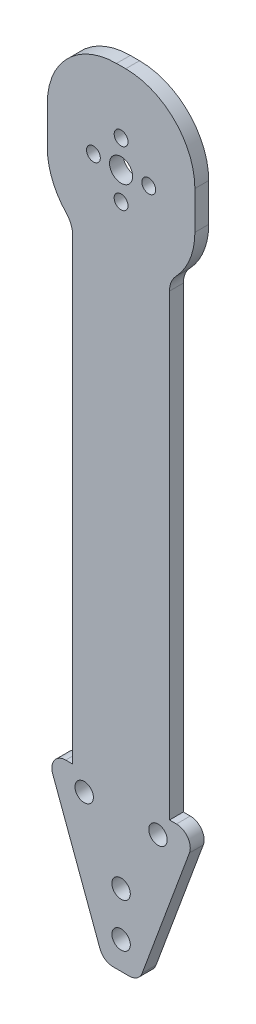
SolidWorks part; units mm, degrees
ref_plane "Alzado" through (0, 0, 0) normal (0, 0, 1) x (1, 0, 0)
ref_plane "Planta" through (0, 0, 0) normal (0, 1, 0) x (1, 0, 0)
ref_plane "Vista lateral" through (0, 0, 0) normal (1, 0, 0) x (0, 0, -1)
sketch "Croquis1" plane through (0, 0, 0) normal (0, 0, 1) x (1, 0, 0)
  line L0 (0, 0) -> (0, 170) construction
  line L1 (1.7626, 0) -> (-1.7626, 0)
  line L2 (-4.5763, 1.9593) -> (-14.816, 29.6448)
  line L3 (-12.0023, 33.6854) -> (-10.5, 33.6854)
  line L4 (-10.5, 33.6854) -> (-10.5, 133)
  line L6 (-16, 146.775) -> (-16, 155)
  line L7 (-1, 170) -> (1, 170)
  line L8 (16, 146.775) -> (16, 155)
  line L10 (10.5, 33.6854) -> (10.5, 133)
  line L11 (12.0023, 33.6854) -> (10.5, 33.6854)
  line L12 (4.5763, 1.9593) -> (14.816, 29.6448)
  line L13 (9.5, 29.6854) -> (0, 4) construction
  line L14 (0, 4) -> (-9.5, 29.6854) construction
  line L15 (-9.5, 29.6854) -> (9.5, 29.6854) construction
  line L16 (-16, 146.775) -> (16, 146.775) construction
  line L17 (-6, 150.5) -> (0, 150.5) construction
  circle A0 centre (0, 6) radius 2
  circle A1 centre (0, 15.55) radius 1.5 construction
  circle A2 centre (-8, 29.6854) radius 1.5 construction
  circle A3 centre (8, 29.6854) radius 1.5 construction
  arc A4 (10.5, 133) -> (11.875, 136.4437) centre (15.5, 133) cw
  arc A5 (-11.875, 136.4437) -> (-10.5, 133) centre (-15.5, 133) cw
  arc A6 (1, 170) -> (16, 155) centre (1, 155) cw
  arc A7 (-16, 155) -> (-1, 170) centre (-1, 155) cw
  arc A8 (4.5763, 1.9593) -> (1.7626, 0) centre (1.7626, 3) cw
  arc A9 (-4.5763, 1.9593) -> (-1.7626, 0) centre (-1.7626, 3) ccw
  arc A10 (14.816, 29.6448) -> (12.0023, 33.6854) centre (12.0023, 30.6854) ccw
  arc A11 (-14.816, 29.6448) -> (-12.0023, 33.6854) centre (-12.0023, 30.6854) cw
  arc A12 (-16, 146.775) -> (-11.875, 136.4437) centre (-1, 146.775) ccw
  arc A13 (16, 146.775) -> (11.875, 136.4437) centre (1, 146.775) cw
  circle A14 centre (0, 150.5) radius 2.5
  circle A16 centre (0, 144.5) radius 1.5
  circle A17 centre (-6, 150.5) radius 1.5
  circle A18 centre (0, 156.5) radius 1.5
  circle A19 centre (6, 150.5) radius 1.5
  circle A20 centre (-8, 29.6854) radius 2
  circle A21 centre (8, 29.6854) radius 2
  circle A22 centre (0, 15.55) radius 2
  point P3 (-16, 150.8875)
  point P13 (0, 148)
  point P24 (0, 4)
  point P25 (8, 31.1854)
  point P26 (-8, 31.1854)
  point P27 (-9.5, 29.6854)
  point P28 (9.5, 29.6854)
  point P31 (-7.5, 150.5)
  point P35 (2.5, 150.5)
  point P37 (0, 17.05)
  point P39 (16, 170)
  point P42 (-16, 170)
  point P45 (3.8516, 0)
  point P48 (-3.8516, 0)
  point P51 (16.3105, 33.6854)
  point P54 (-16.3105, 33.6854)
  point P64 (0, 143)
  point P65 (0, 153)
  dimension "D7" = 3
  dimension "D8" = 4
  dimension "D13" = 5
  dimension "D14" = 15
  dimension "D15" = 3
  dimension "D16" = 15
  dimension "D2" = 15
  dimension "D19" = 5
  dimension "D23" = 3
  dimension "D1" = 170
  dimension "D3" = 21
  dimension "D4" = 32
  dimension "D5" = 19
  dimension "D6" = 25
  dimension "D9" = 25
  dimension "D10" = 4
  dimension "D11" = 4
  dimension "D12" = 9.55
  dimension "D17" = 37
  dimension "D18" = 37
  dimension "D20" = 22
  dimension "D21" = 10
  dimension "D22" = 10
  dimension "D24" = 5
  dimension "D25" = 0.5
extrude "Saliente-Extruir1" add sketch "Croquis1" along normal blind 3 contours L10 A4 A13 L8 A6 L7 A7 L6 A12 A5 L4 L3 A11 L2 A9 L1 A8 L12 A10 L11 | A19 | A18 | A17 | A16 | A3 | A1 | A2 | A0 | A22 | A20 | A21 | A14
